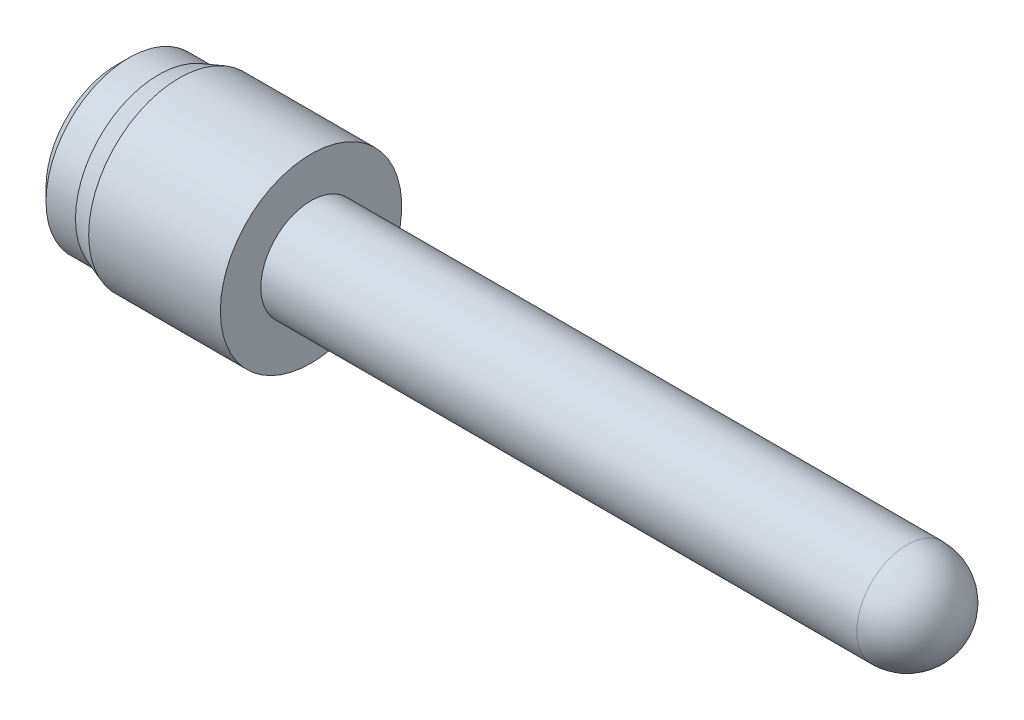
SolidWorks part; units mm, degrees
material "Brass Alloy 385"
ref_plane "Front Plane" through (0, 0, 0) normal (0, 0, 1) x (1, 0, 0)
ref_plane "Top Plane" through (0, 0, 0) normal (0, 1, 0) x (1, 0, 0)
ref_plane "Right Plane" through (0, 0, 0) normal (1, 0, 0) x (0, 0, -1)
sketch "Sketch1" plane through (0, 0, 0) normal (0, 0, 1) x (1, 0, 0)
  line L0 (0, 0) -> (0, 0.2857)
  line L1 (0.254, 0.367) -> (0.1703, 0.3365)
  line L2 (0.254, 0.367) -> (0.7874, 0.367)
  line L3 (0.0508, 0.3365) -> (0, 0.2857)
  line L4 (0.1703, 0.3365) -> (0.0508, 0.3365)
  line L6 (0.7874, 0.2032) -> (3.2004, 0.2032)
  line L7 (0, 0) -> (3.4036, 0)
  line L8 (0, 0) -> (3.4036, 0) construction
  line L9 (0, 0) -> (3.4036, 0) construction
  line L10 (0.7874, 0.367) -> (0.7874, 0.2032)
  arc A0 (3.4036, 0) -> (3.2004, 0.2032) centre (3.2004, 0) ccw
  point P0 (0.5334, 0.367)
  point P1 (0.7874, 0.367)
  point P6 (0.5334, 0.2032)
  point P11 (0, 0.2857)
  point P13 (3.1496, 0.3048)
revolve "RevolutionAngle1" add sketch "Sketch1" angle 360 about L9
